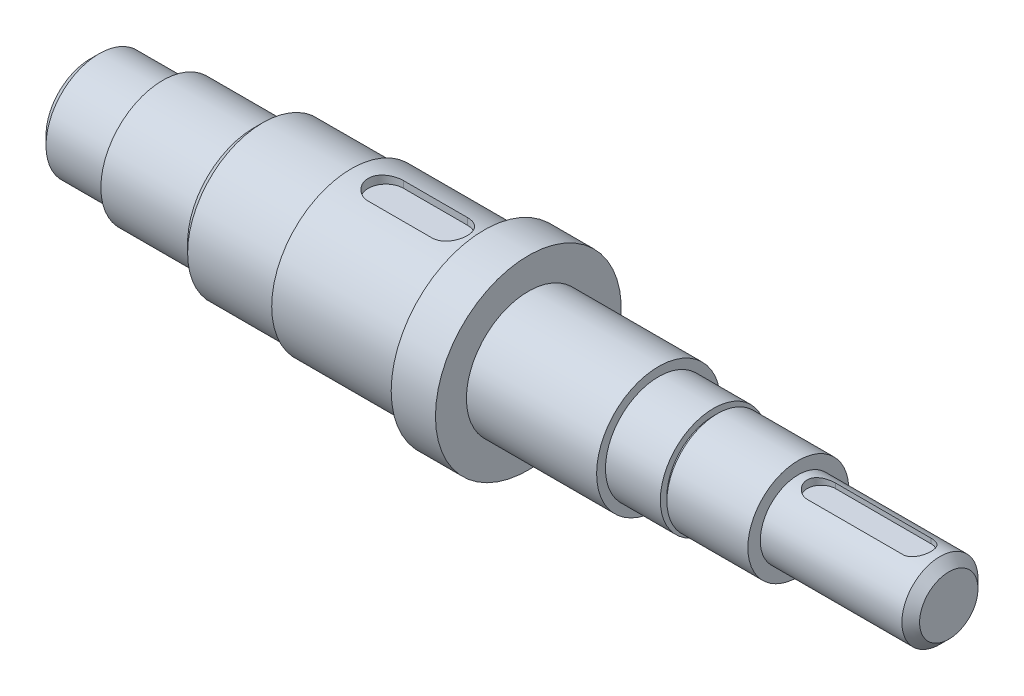
SolidWorks part; units mm, degrees
ref_plane "Front Plane" through (0, 0, 0) normal (0, 0, 1) x (1, 0, 0)
ref_plane "Top Plane" through (0, 0, 0) normal (0, 1, 0) x (1, 0, 0)
ref_plane "Right Plane" through (0, 0, 0) normal (1, 0, 0) x (0, 0, -1)
sketch "Sketch2" plane through (0, 0, 0) normal (0, 1, 0) x (1, 0, 0)
  line L0 (242.5, 0) -> (-242.5, 0)
  line L1 (-242.5, 0) -> (-242.5, 30)
  line L2 (-20, 52.5) -> (5, 52.5)
  line L3 (242.5, 21.5) -> (242.5, 0)
  line L4 (-418.8225, 0) -> (324.1035, 0) construction
  line L5 (-242.5, 30) -> (-201.5, 30)
  line L6 (-201.5, 30) -> (-201.5, 35)
  line L7 (-201.5, 35) -> (-150, 35)
  line L8 (-150, 35) -> (-150, 42.5)
  line L9 (-150, 42.5) -> (-95, 42.5)
  line L10 (-95, 42.5) -> (-95, 45)
  line L11 (-95, 45) -> (-20, 45)
  line L12 (-20, 45) -> (-20, 52.5)
  line L13 (5, 52.5) -> (5, 35)
  line L14 (5, 35) -> (78.55, 35)
  line L15 (78.55, 35) -> (78.55, 30)
  line L16 (78.55, 30) -> (109.55, 30)
  line L17 (109.55, 30) -> (109.55, 26.3)
  line L18 (109.55, 26.3) -> (111.75, 26.3)
  line L19 (111.75, 26.3) -> (111.75, 28.5)
  line L20 (111.75, 28.5) -> (157.5, 28.5)
  line L21 (157.5, 28.5) -> (157.5, 21.5)
  line L22 (157.5, 21.5) -> (242.5, 21.5)
  point P4 (0, 0)
  dimension "D1" = 52.5
  dimension "D2" = 485
  dimension "D3" = 30
  dimension "D4" = 41
  dimension "D5" = 35
  dimension "D6" = 92.5
  dimension "D7" = 42.5
  dimension "D8" = 147.5
  dimension "D9" = 45
  dimension "D10" = 222.5
  dimension "D11" = 21.5
  dimension "D12" = 85
  dimension "D13" = 28.5
  dimension "D14" = 130.75
  dimension "D16" = 2.2
  dimension "D18" = 30
  dimension "D19" = 31
  dimension "D20" = 35
  dimension "D21" = 237.5
revolve "Revolve1" add sketch "Sketch2" angle 360 about L4
chamfer "Chamfer1" distance 5 angle 45 3 edges at (-242.5, 0, 30) (-150, 0, 42.5) (242.5, 0, 21.5)
sketch "Sketch3" plane through (0, 0, 0) normal (0, 1, 0) x (1, 0, 0)
  line L0 (-75.5, 0) -> (-39.5, 0) construction
  line L1 (-75.5, 10) -> (-39.5, 10)
  line L2 (-75.5, -10) -> (-39.5, -10)
  line L3 (-20, 52.5) -> (-20, -52.5) construction
  arc A0 (-75.5, 10) -> (-75.5, -10) centre (-75.5, 0) ccw
  arc A1 (-39.5, -10) -> (-39.5, 10) centre (-39.5, 0) ccw
  point P3 (-57.5, 0)
  point P8 (-85.5, 0)
  point P9 (-29.5, 0)
  dimension "D1" = 56
  dimension "D2" = 37.5
  dimension "D3" = 20
extrude "Cut-Extrude1" cut sketch "Sketch3" against normal mid plane 9.8 from offset 45
sketch "Sketch4" plane through (0, 0, 0) normal (0, 1, 0) x (1, 0, 0)
  line L0 (170.5, 0) -> (224.5, 0) construction
  line L1 (170.5, 8) -> (224.5, 8)
  line L2 (170.5, -8) -> (224.5, -8)
  line L6 (242.5, -16.5) -> (242.5, 16.5) construction
  arc A0 (170.5, 8) -> (170.5, -8) centre (170.5, 0) ccw
  arc A1 (224.5, -8) -> (224.5, 8) centre (224.5, 0) ccw
  point P3 (197.5, 0)
  point P10 (162.5, 0)
  point P11 (232.5, 0)
  dimension "D1" = 70
  dimension "D2" = 10
  dimension "D3" = 16
extrude "Cut-Extrude2" cut sketch "Sketch4" against normal mid plane 8.6 from offset 21.5
